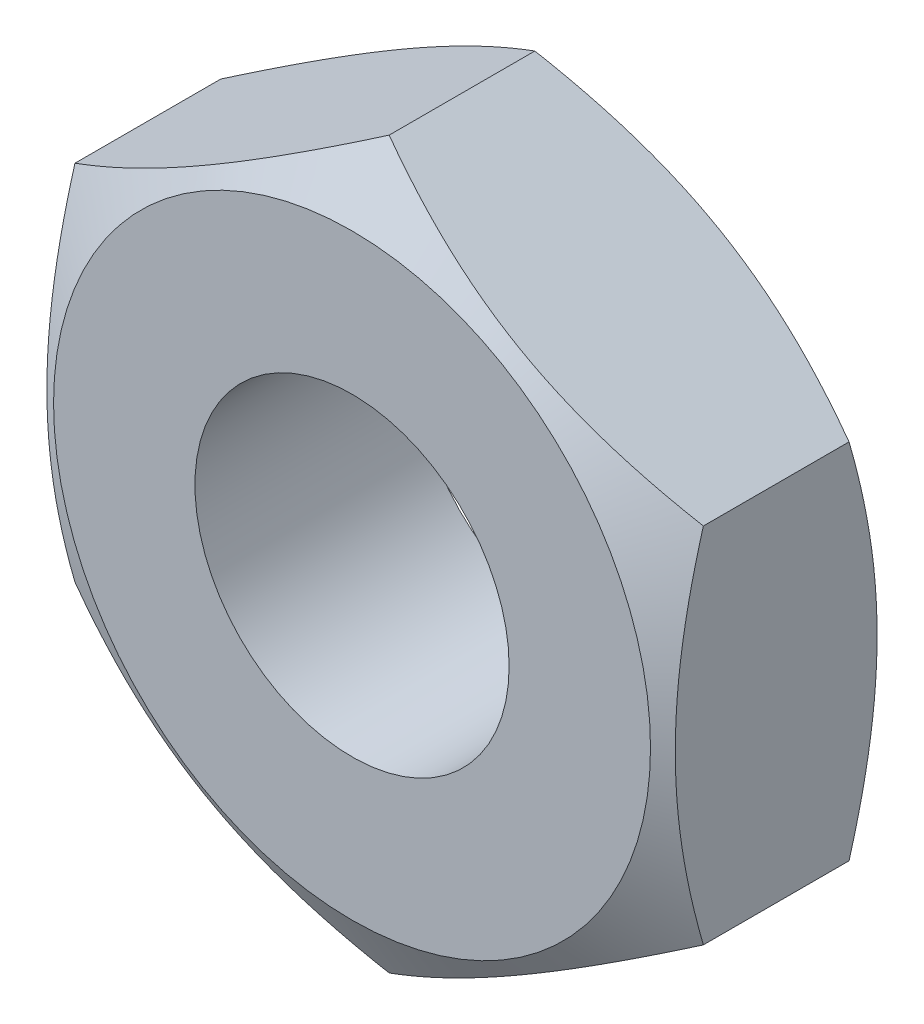
SolidWorks part; units mm, degrees
ref_plane "Спереди" through (0, 0, 0) normal (0, 0, 1) x (1, 0, 0)
ref_plane "Сверху" through (0, 0, 0) normal (0, 1, 0) x (1, 0, 0)
ref_plane "Справа" through (0, 0, 0) normal (1, 0, 0) x (0, 0, -1)
sketch "Sketch1" plane through (0, 0, 0) normal (0, 0, 1) x (1, 0, 0)
  line L7 (0, 2.8868) -> (-2.5, 1.4434)
  line L8 (-2.5, 1.4434) -> (-2.5, -1.4434)
  line L9 (-2.5, -1.4434) -> (0, -2.8868)
  line L10 (0, -2.8868) -> (2.5, -1.4434)
  line L11 (2.5, -1.4434) -> (2.5, 1.4434)
  line L12 (2.5, 1.4434) -> (0, 2.8868)
  circle A0 centre (0, 0) radius 1.25
  circle A1 centre (0, 0) radius 2.5 construction
extrude "Extrude1" add sketch "Sketch1" along normal blind 1.75
sketch "Sketch2" plane through (0, 0, 0) normal (1, 0, 0) x (0, 0, -1)
  line L0 (0, 2.375) -> (-0.7615, 3.694)
  line L1 (0, 2.375) -> (0, 5.1947)
  line L2 (-1.75, 0) -> (0, 0)
  line L3 (-1.75, -1.4434) -> (-1.75, 1.4434) construction
  line L4 (-0.875, 0) -> (-0.875, -3.3526) construction
  line L5 (-1.75, 2.375) -> (-1.75, 5.1947)
  line L6 (-1.75, 2.375) -> (-0.9885, 3.694)
  line L7 (-3.1638, 3.5044) -> (0.8049, 3.5044)
  circle A0 centre (0, 0) radius 2.375
  circle A1 centre (-1.75, 0) radius 2.375
revolve "Cut-Revolve1" cut sketch "Sketch2" angle 360 about L2
